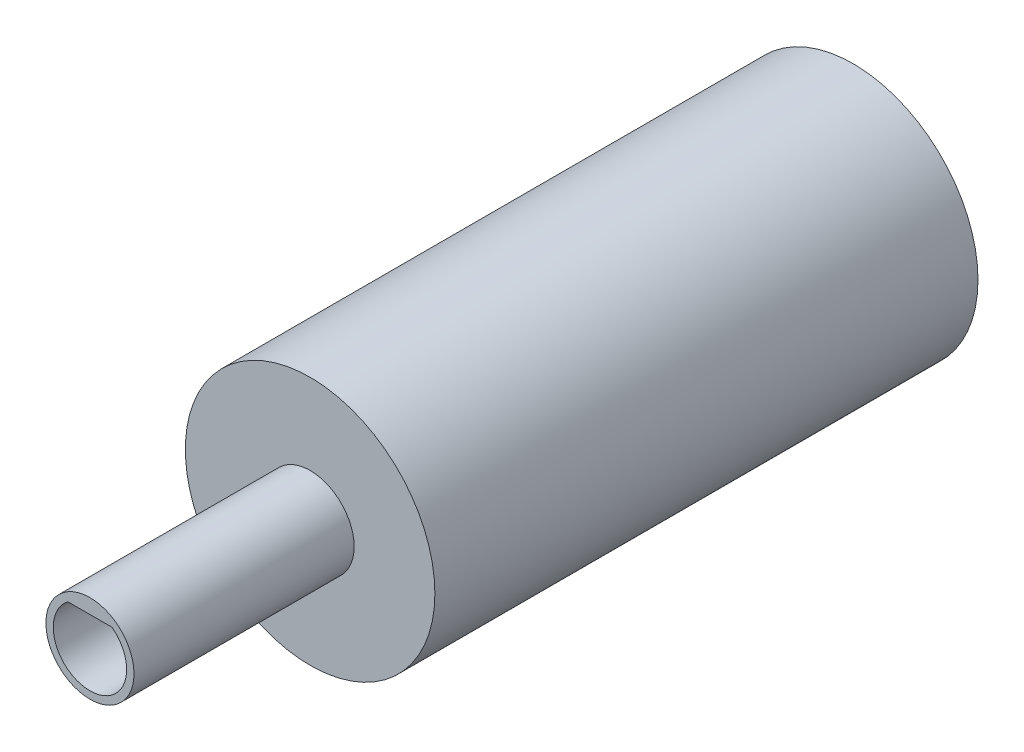
SolidWorks part; units mm, degrees
other "Markup1"
sketch "Sketch6" plane through (-8.5, 8.5, 15) normal (-0.1925, 0.435, 0.8796) x (-0.1405, -0.8994, 0.414)
material "Alloy Steel"
ref_plane "Front Plane" through (0, 0, 0) normal (0, 0, 1) x (1, 0, 0)
ref_plane "Top Plane" through (0, 0, 0) normal (0, 1, 0) x (1, 0, 0)
ref_plane "Right Plane" through (0, 0, 0) normal (1, 0, 0) x (0, 0, -1)
sketch "Sketch1" plane through (0, 0, 0) normal (0, 0, 1) x (1, 0, 0)
  line L0 (1.5, 2) -> (-1.5, 2)
  circle A0 centre (0, 0) radius 3
  arc A1 (-1.5, 2) -> (1.5, 2) centre (0, 0) ccw
  dimension "D1" = 5
  dimension "D2" = 6
  dimension "D3" = 3
extrude "Boss-Extrude1" add sketch "Sketch1" along normal blind 15
sketch "Sketch2" plane through (0, 0, 0) normal (0, 0, -1) x (-1, 0, 0)
  circle A0 centre (0, 0) radius 8.5
  dimension "D1" = 17
extrude "Boss-Extrude2" add sketch "Sketch2" along normal blind 5.25
sketch "Sketch3" plane through (0, 0, -5.25) normal (0, 0, -1) x (-1, 0, 0)
  circle A0 centre (0, 0) radius 8.5
  dimension "D1" = 17
extrude "Boss-Extrude4" add sketch "Sketch3" along normal blind 31.75
sketch "Sketch13" plane through (0, 0, -37) normal (0, 0, -1) x (-1, 0, 0)
  line L0 (-2.39, 7.5718) -> (-2.39, 4.7618)
  line L1 (-2.39, 4.7618) -> (2.39, 4.7618)
  line L2 (2.39, 4.7618) -> (2.39, 7.5718)
  circle A0 centre (0, 0) radius 7.94
  dimension "D1" = 15.88
  dimension "D2" = 4.78
  dimension "D3" = 2.81
extrude "Cut-Extrude4" cut sketch "Sketch13" against normal blind 31.75 contours L0 A0 L2 L1
sketch "Sketch14" plane through (0, 4.7618, 0) normal (0, -1, 0) x (1, 0, 0)
  line L0 (-2.39, -34.61) -> (2.39, -34.61)
  line L1 (-2.39, -5.25) -> (-2.39, -37) construction
  line L2 (2.39, -5.25) -> (2.39, -37) construction
  line L3 (2.39, -37) -> (-2.39, -37) construction
  line L4 (-2.39, -34.61) -> (-2.39, -37)
  line L5 (-2.39, -37) -> (2.39, -37)
  line L6 (2.39, -37) -> (2.39, -34.61)
  arc A0 (-2.39, -34.61) -> (2.39, -34.61) centre (0, -34.61) ccw
  line M2 (-2.39, -37) -> (2.39, -37)
  line M3 (2.39, -37) -> (2.39, -5.25)
  line M5 (-2.39, -5.25) -> (-2.39, -37)
  dimension "D2" = 2.39
  dimension "D1" = 2.39
extrude "Cut-Extrude5" cut sketch "Sketch14" against normal up to surface (2.81 mm away) contours A0 L5 M3 | A0 M5 M2
